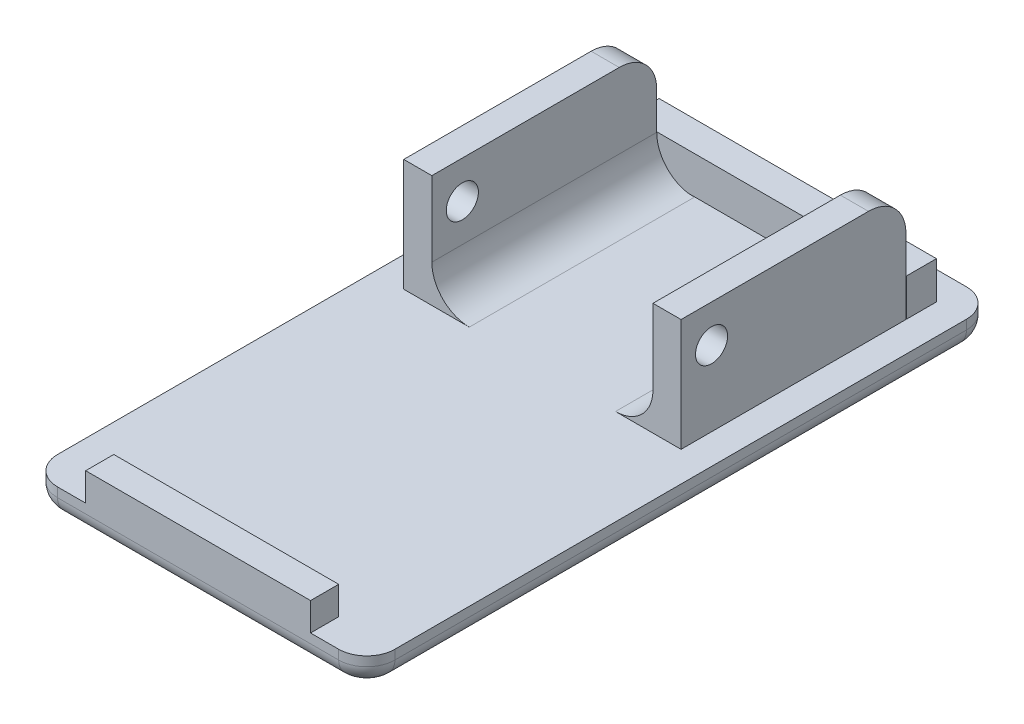
SolidWorks part; units mm, degrees
ref_plane "前视基准面" through (0, 0, 0) normal (0, 0, 1) x (1, 0, 0)
ref_plane "上视基准面" through (0, 0, 0) normal (0, 1, 0) x (1, 0, 0)
ref_plane "右视基准面" through (0, 0, 0) normal (1, 0, 0) x (0, 0, -1)
sketch "草图1" plane through (0, 0, 0) normal (0, 1, 0) x (1, 0, 0)
  line L1 (-9, 16.75) -> (9, 16.75)
  line L2 (-9, 16.75) -> (-9, -16.75)
  line L3 (-9, -16.75) -> (9, -16.75)
  line L4 (9, 16.75) -> (9, -16.75)
  dimension "D1" = 18
  dimension "D2" = 33.5
  dimension "D3" = 16.75
  dimension "D4" = 9
extrude "凸台-拉伸1" add sketch "草图1" along normal blind 1.5
fillet "圆角1" radius 1.5 4 edges at (9, 0.75, 16.75) (-9, 0.75, 16.75) (9, 0.75, -16.75) (-9, 0.75, -16.75)
sketch "草图2" plane through (0, 1.5, 0) normal (0, 1, 0) x (1, 0, 0)
  line L0 (-9, 15.25) -> (-9, -15.25) construction
  line L1 (-7.4, 13.6224) -> (-5.9, 13.6224)
  line L2 (-7.4, 13.6224) -> (-7.4, 1.6224)
  line L3 (-7.4, 1.6224) -> (-5.9, 1.6224)
  line L4 (-5.9, 13.6224) -> (-5.9, 1.6224)
  line L5 (0, 13.01) -> (0, -10.9624) construction
  line L6 (5.9, 13.6224) -> (5.9, 1.6224)
  line L7 (7.4, 1.6224) -> (5.9, 1.6224)
  line L8 (7.4, 13.6224) -> (7.4, 1.6224)
  line L9 (7.4, 13.6224) -> (5.9, 13.6224)
  dimension "D1" = 1.5
  dimension "D2" = 1.6
  dimension "D3" = 12
extrude "凸台-拉伸2" add sketch "草图2" along normal blind 6
sketch "草图3" plane through (0, 1.5, 0) normal (0, 1, 0) x (1, 0, 0)
  line L0 (7.4, 1.6224) -> (7.4, 13.6224) construction
  line L1 (-7.4, 15.25) -> (7.4, 15.25)
  line L2 (-7.4, 15.25) -> (-7.4, 13.65)
  line L3 (-7.4, 13.65) -> (7.4, 13.65)
  line L4 (7.4, 15.25) -> (7.4, 13.65)
  line L5 (7.4, 1.6224) -> (7.4, 13.6224) construction
  line L6 (7.5, 16.75) -> (-7.5, 16.75) construction
  line L7 (-9, 15.25) -> (-9, -15.25) construction
  dimension "D1" = 1.5
  dimension "D2" = 1.6
  dimension "D3" = 1.6
extrude "凸台-拉伸3" add sketch "草图3" along normal blind 2
fillet "圆角2" radius 2 4 edges at (-6.65, 7.5, -13.6224) (6.65, 7.5, -13.6224) (-5.9, 1.5, -7.6224) (5.9, 1.5, -7.6224)
sketch "草图4" plane through (7.4, 0, 0) normal (1, 0, 0) x (0, 0, -1)
  line L0 (15.25, 0) -> (15.25, 1.5) construction
  line L1 (-15.25, 1.5) -> (15.25, 1.5) construction
  circle A0 centre (3.25, 5.5) radius 0.8565
  dimension "D1" = 12
  dimension "D2" = 4
extrude "切除-拉伸1" cut sketch "草图4" against normal blind 18
sketch "草图5" plane through (0, 1.5, 0) normal (0, 1, 0) x (1, 0, 0)
  line L7 (-7.5, -16.75) -> (7.5, -16.75) construction
  line L12 (-6, -16.75) -> (6, -16.75)
  line L13 (-6, -16.75) -> (-6, -15.25)
  line L14 (-6, -15.25) -> (6, -15.25)
  line L15 (6, -16.75) -> (6, -15.25)
  line L16 (-9, 15.25) -> (-9, -15.25) construction
  dimension "D1" = 1.5
  dimension "D2" = 12
  dimension "D3" = 3
extrude "凸台-拉伸4" add sketch "草图5" along normal blind 1.5
fillet "圆角3" radius 1 8 edges at (8.5607, 0, -16.3107) (0, 0, -16.75) (-8.5607, 0, -16.3107) (-9, 0, 0) (-8.5607, 0, 16.3107) (0, 0, 16.75) (8.5607, 0, 16.3107) (9, 0, 0)
